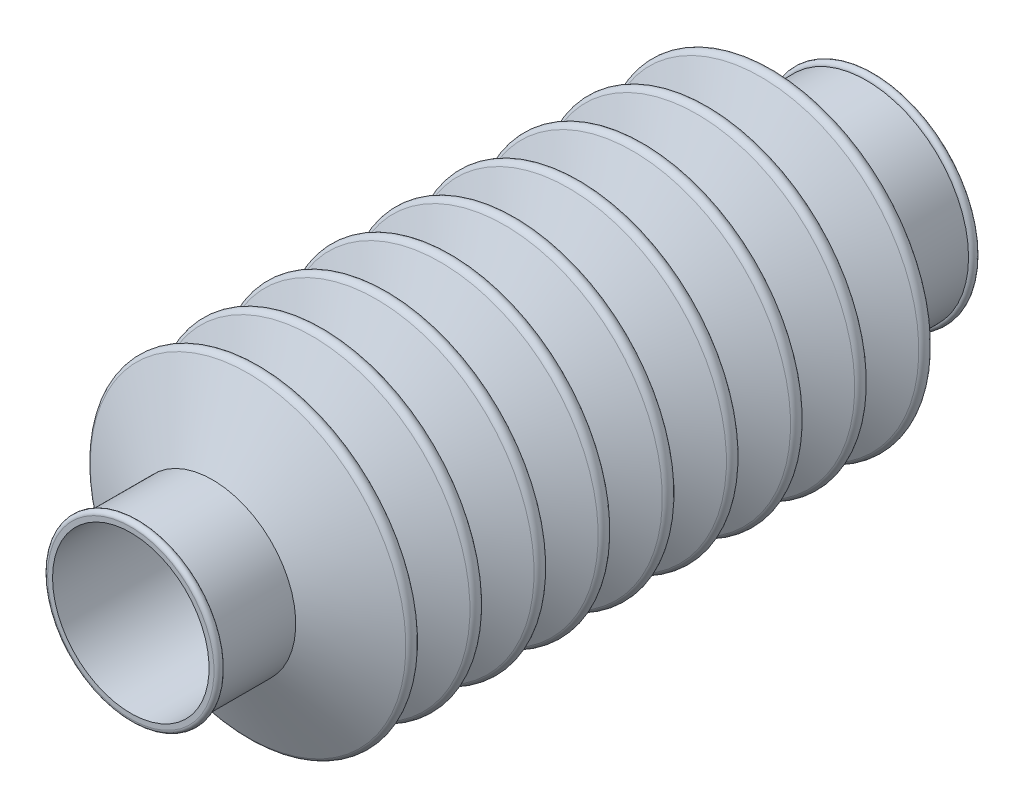
SolidWorks part; units mm, degrees
material "Rubber"
ref_plane "Front Plane" through (0, 0, 0) normal (0, 0, 1) x (1, 0, 0)
ref_plane "Top Plane" through (0, 0, 0) normal (0, 1, 0) x (1, 0, 0)
ref_plane "Right Plane" through (0, 0, 0) normal (1, 0, 0) x (0, 0, -1)
sketch "Sketch2" plane through (0, 0, 0) normal (0, 1, 0) x (1, 0, 0)
  line L0 (0, 18) -> (0, -107.6242) construction
  line L1 (-12.7, -107.6242) -> (12.7, -107.6242) construction
  line L2 (16.5723, -15.0761) -> (25.6011, -10.7772)
  line L3 (15.875, 18) -> (16.5723, 18)
  line L4 (15.875, 0) -> (15.875, 26.3062) construction
  line L5 (16.5723, 16.7311) -> (16.5723, 5.7311)
  line L6 (-16.7573, 0.5293) -> (59.1316, 0.5293) construction
  line L7 (15.875, 18) -> (15.875, -2.8424)
  line L8 (16.5723, 5.7311) -> (25.6011, 1.4322)
  line L9 (16.5723, -4.6725) -> (25.6011, -0.3736)
  line L10 (16.5723, -4.6725) -> (25.6011, -8.9715)
  line L11 (16.5723, -25.4797) -> (25.6011, -21.1808)
  line L12 (16.5723, -15.0761) -> (25.6011, -19.3751)
  line L13 (16.5723, -35.8834) -> (25.6011, -31.5844)
  line L14 (16.5723, -25.4797) -> (25.6011, -29.7787)
  line L15 (16.5723, -46.287) -> (25.6011, -41.988)
  line L16 (16.5723, -35.8834) -> (25.6011, -40.1823)
  line L17 (16.5723, -56.6906) -> (25.6011, -52.3916)
  line L18 (16.5723, -46.287) -> (25.6011, -50.5859)
  line L19 (16.5723, -67.0942) -> (25.6011, -62.7953)
  line L20 (16.5723, -56.6906) -> (25.6011, -60.9895)
  line L21 (16.5723, -77.4978) -> (25.6011, -73.1989)
  line L22 (16.5723, -67.0942) -> (25.6011, -71.3931)
  line L23 (16.5723, -87.9014) -> (25.6011, -83.6025)
  line L24 (16.5723, -77.4978) -> (25.6011, -81.7967)
  line L25 (15.875, -2.8424) -> (12.7, -2.8424)
  line L26 (12.7, -106.1242) -> (12.7, 246.4758) construction
  line L27 (12.7, -2.8424) -> (12.7, -102.6242)
  line L28 (12.7, -102.6242) -> (13.5, -102.6242)
  line L29 (16.5723, -87.9014) -> (13.5, -89.3642)
  line L30 (13.5, -101.3642) -> (13.5, -89.3642)
  arc A0 (16.5723, 18) -> (16.5723, 16.7311) centre (16.5723, 17.3655) cw
  arc A1 (25.6011, 1.4322) -> (25.6011, -0.3736) centre (25.1712, 0.5293) cw
  arc A2 (25.6011, -8.9715) -> (25.6011, -10.7772) centre (25.1712, -9.8743) cw
  arc A3 (25.6011, -19.3751) -> (25.6011, -21.1808) centre (25.1712, -20.2779) cw
  arc A4 (25.6011, -29.7787) -> (25.6011, -31.5844) centre (25.1712, -30.6815) cw
  arc A5 (25.6011, -40.1823) -> (25.6011, -41.988) centre (25.1712, -41.0852) cw
  arc A6 (25.6011, -50.5859) -> (25.6011, -52.3916) centre (25.1712, -51.4888) cw
  arc A7 (25.6011, -60.9895) -> (25.6011, -62.7953) centre (25.1712, -61.8924) cw
  arc A8 (25.6011, -71.3931) -> (25.6011, -73.1989) centre (25.1712, -72.296) cw
  arc A9 (25.6011, -81.7967) -> (25.6011, -83.6025) centre (25.1712, -82.6996) cw
  arc A10 (13.5, -102.6242) -> (13.5, -101.3642) centre (13.5, -101.9942) ccw
  dimension "D3" = 0.6345
  dimension "D4" = 10
  dimension "D7" = 9
  dimension "D8" = 0.63
  dimension "D6" = 1
  dimension "D1" = 18
  dimension "D2" = 0.6973
  dimension "D5" = 11
  dimension "D9" = 0.8
  dimension "D10" = 5
  dimension "D11" = 12
revolve "Revolve1" add sketch "Sketch2" angle 360 about L0
